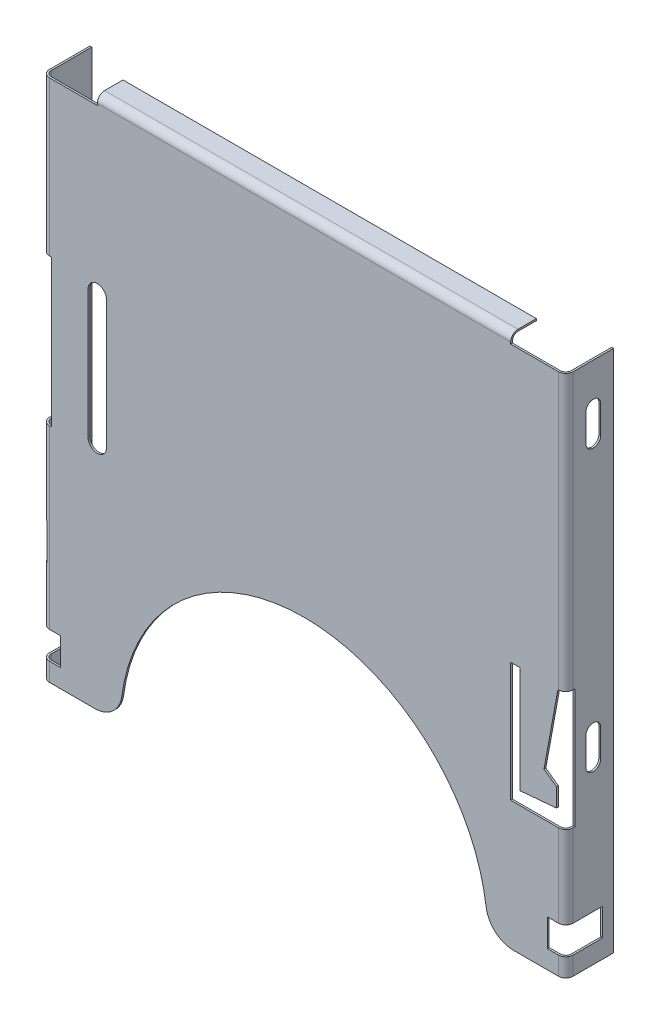
SolidWorks part; units mm, degrees
material "Liga 1060"
ref_plane "Plano frontal" through (0, 0, 0) normal (0, 0, 1) x (1, 0, 0)
ref_plane "Plano superior" through (0, 0, 0) normal (0, 1, 0) x (1, 0, 0)
ref_plane "Plano direito" through (0, 0, 0) normal (1, 0, 0) x (0, 0, -1)
sketch "Esboço1" plane through (0, 0, 0) normal (0, 0, 1) x (1, 0, 0)
  line L0 (0, 0) -> (0, -18.3273) construction
  line L1 (-14.25, -14.5) -> (-11.4018, -14.5)
  line L2 (-14.25, -14.5) -> (-14.25, 14.5)
  line L3 (-14.25, 14.5) -> (14.25, 14.5)
  line L4 (14.25, -14.5) -> (14.25, 14.5)
  line L5 (-14.25, -14.5) -> (14.25, 14.5) construction
  line L6 (-14.25, 14.5) -> (14.25, -14.5) construction
  line L7 (11.4018, -14.5) -> (14.25, -14.5)
  arc A0 (9.9146, -13.1957) -> (-9.9146, -13.1957) centre (0, -14.5) ccw
  arc A1 (11.4018, -14.5) -> (9.9146, -13.1957) centre (11.4018, -13) cw
  arc A2 (-11.4018, -14.5) -> (-9.9146, -13.1957) centre (-11.4018, -13) ccw
  point P0 (0, 0)
  point P13 (10, -14.5)
  dimension "D3" = 20
  dimension "D4" = 1.5
  dimension "D1" = 29
  dimension "D2" = 28.5
extrude "Ressalto-extrusão1" add sketch "Esboço1" along normal blind 2.6
fillet "Filete1" radius 0.4 3 edges at (14.25, 0, 2.6) (0, 14.5, 2.6) (-14.25, 0, 2.6)
shell "Casca1" thickness 0.1
sketch "Esboço2" plane through (0, -14.5, 0) normal (0, -1, 0) x (1, 0, 0)
  line L0 (-14.25, 0) -> (-11.4018, 0) construction
  line L1 (-14.15, 0) -> (14.15, 0)
  line L2 (-14.15, 0) -> (-14.15, 2.2)
  line L3 (-13.85, 2.5) -> (13.85, 2.5)
  line L4 (14.15, 0) -> (14.15, 2.2)
  arc A0 (14.15, 2.2) -> (13.85, 2.5) centre (13.85, 2.2) ccw construction
  arc A1 (14.15, 2.2) -> (13.85, 2.5) centre (13.85, 2.2) ccw
  arc A2 (-13.85, 2.5) -> (-14.15, 2.2) centre (-13.85, 2.2) ccw construction
  arc A3 (-13.85, 2.5) -> (-14.15, 2.2) centre (-13.85, 2.2) ccw
extrude "Corte-extrusão1" cut sketch "Esboço2" against normal blind 12.6
sketch "Esboço3" plane through (0, 0, 2.6) normal (0, 0, 1) x (1, 0, 0)
  line L0 (-11.25, 5.1) -> (-11.25, -1.9) construction
  line L1 (-10.75, 5.1) -> (-10.75, -1.9)
  line L2 (-11.75, 5.1) -> (-11.75, -1.9)
  line L3 (13.85, 14.1) -> (-13.85, 14.1) construction
  line L4 (-14.25, -14.5) -> (-14.25, 14.5) construction
  line L5 (11.25, -1) -> (11.25, -7.5)
  line L6 (11.25, -7.5) -> (14.25, -7.5)
  line L7 (14.25, -7.5) -> (14.25, -1)
  line L8 (13.8212, -1) -> (13.066, -5.125)
  line L9 (13.066, -5.125) -> (13.75, -5.625)
  line L10 (13.75, -5.625) -> (13.75, -6.625)
  line L11 (13.75, -6.625) -> (11.75, -6.8)
  line L12 (11.75, -6.8) -> (11.75, -1)
  line L13 (11.75, -1) -> (11.25, -1)
  line L14 (14.25, 14.5) -> (14.25, -14.5) construction
  line L15 (14.25, -14.5) -> (14.25, 14.5) construction
  line L16 (13.8212, -1) -> (14.25, -1)
  line L17 (11.4018, -14.5) -> (13.85, -14.5) construction
  line L19 (14.25, -12) -> (13.25, -12)
  line L20 (14.25, -12) -> (14.25, -13.5)
  line L21 (14.25, -13.5) -> (13.25, -13.5)
  line L22 (13.25, -12) -> (13.25, -13.5)
  line L23 (0, 0) -> (0, -6.8) construction
  line L24 (-13.25, -12) -> (-13.25, -13.5)
  line L25 (-14.25, -13.5) -> (-13.25, -13.5)
  line L26 (-14.25, -12) -> (-14.25, -13.5)
  line L27 (-14.25, -12) -> (-13.25, -12)
  line L29 (-14.25, -9) -> (-14.05, -9)
  line L30 (-14.25, -9) -> (-14.25, -7)
  line L31 (-14.25, -7) -> (-14.05, -7)
  line L32 (-14.05, -9) -> (-14.05, -7)
  line L33 (-13.85, -14.5) -> (-11.4018, -14.5) construction
  line L34 (14.25, 14.5) -> (11.25, 14.5)
  line L35 (14.25, 14.5) -> (14.25, 14)
  line L36 (14.25, 14) -> (11.25, 14)
  line L37 (11.25, 14.5) -> (11.25, 14)
  line L38 (-11.25, 14.5) -> (-11.25, 14)
  line L39 (-14.25, 14) -> (-11.25, 14)
  line L40 (-14.25, 14.5) -> (-14.25, 14)
  line L41 (-14.25, 14.5) -> (-11.25, 14.5)
  arc A0 (-10.75, 5.1) -> (-11.75, 5.1) centre (-11.25, 5.1) ccw
  arc A1 (-11.75, -1.9) -> (-10.75, -1.9) centre (-11.25, -1.9) ccw
  point P2 (-11.25, 1.6)
  dimension "D1" = 7
  dimension "D2" = 9
  dimension "D3" = 1
  dimension "D4" = 3
  dimension "D5" = 6.5
  dimension "D6" = 0.5
  dimension "D7" = 85
  dimension "D8" = 0.7
  dimension "D9" = 2
  dimension "D10" = 1
  dimension "D11" = 0.5
  dimension "D12" = 3
  dimension "D13" = 7
  dimension "D14" = 1.5
  dimension "D15" = 1
  dimension "D16" = 1
  dimension "D17" = 2
  dimension "D18" = 5.5
  dimension "D19" = 0.2
  dimension "D20" = 0.5
  dimension "D21" = 3
extrude "Corte-extrusão2" cut sketch "Esboço3" against normal blind 0.5
sketch "Esboço4" plane through (0, 14.5, 0) normal (0, 1, 0) x (1, 0, 0)
  line L0 (-11.25, -2.4) -> (-11.25, -1.2)
  line L1 (11.25, -1.2) -> (11.25, -2.2)
  line L2 (-11.25, -1.2) -> (11.25, -1.2)
  line L3 (11.25, -2.2) -> (14.25, -2.2)
  line L4 (14.25, -2.2) -> (14.25, 0)
  line L5 (14.25, 0) -> (-14.25, 0)
  line L6 (-14.25, 0) -> (-14.25, -2.4)
  line L7 (-11.25, -2.4) -> (-14.25, -2.4)
  dimension "D1" = 1
extrude "Corte-extrusão3" cut sketch "Esboço4" against normal blind 0.5
sketch "Esboço5" plane through (14.25, 0, 0) normal (1, 0, 0) x (0, 0, -1)
  line L0 (-1.1, -5) -> (-1.1, -3.5) construction
  line L1 (-2.2, -12) -> (-0.6, -12)
  line L2 (-2.2, -12) -> (-2.2, -13.5)
  line L3 (-2.2, -13.5) -> (-0.6, -13.5)
  line L4 (-0.6, -12) -> (-0.6, -13.5)
  line L5 (-1.5, -5) -> (-1.5, -3.5)
  line L6 (-0.7, -5) -> (-0.7, -3.5)
  line L7 (-1.1, 10.25) -> (-1.1, 11.75) construction
  line L8 (-1.5, 10.25) -> (-1.5, 11.75)
  line L9 (-0.7, 10.25) -> (-0.7, 11.75)
  line L10 (0, -14.5) -> (0, 14) construction
  line L11 (-2.2, 14) -> (0, 14) construction
  arc A0 (-1.5, -5) -> (-0.7, -5) centre (-1.1, -5) ccw
  arc A1 (-0.7, -3.5) -> (-1.5, -3.5) centre (-1.1, -3.5) ccw
  arc A2 (-1.5, 10.25) -> (-0.7, 10.25) centre (-1.1, 10.25) ccw
  arc A3 (-0.7, 11.75) -> (-1.5, 11.75) centre (-1.1, 11.75) ccw
  point P8 (-1.1, -4.25)
  point P13 (-1.1, 11)
  dimension "D1" = 1.6
  dimension "D2" = 0.8
  dimension "D3" = 0.7
  dimension "D4" = 0.8
  dimension "D5" = 1.5
  dimension "D6" = 1.5
  dimension "D7" = 3
  dimension "D8" = 18.25
extrude "Corte-extrusão6" cut sketch "Esboço5" against normal through all
sketch "Esboço6" plane through (-14.25, 0, 0) normal (-1, 0, 0) x (0, 0, 1)
  line L0 (1.1, 5.6) -> (0.6, 5.6)
  line L1 (1.5, -7) -> (2.2, -7)
  line L2 (1.5, -7) -> (1.5, -9)
  line L3 (1.5, -9) -> (2.2, -9)
  line L4 (2.2, -7) -> (2.2, -9)
  line L5 (2.1, 5.6) -> (2.1, -1.9)
  line L6 (2.6, 5.6) -> (2.1, 5.6)
  line L7 (2.6, 5.6) -> (2.6, -2.4)
  line L8 (2.6, -2.4) -> (0.6, -2.4)
  line L9 (0.6, 5.6) -> (0.6, -2.4)
  line L10 (2.1, -1.9) -> (1.1, -1.9)
  line L11 (1.1, -1.9) -> (1.1, 5.6)
  line L12 (2.6, 14) -> (2.6, -12) construction
  dimension "D1" = 0.7
  dimension "D2" = 0.5
  dimension "D3" = 0.5
  dimension "D4" = 0.5
  dimension "D5" = 1
extrude "Corte-extrusão7" cut sketch "Esboço6" against normal blind 0.5
